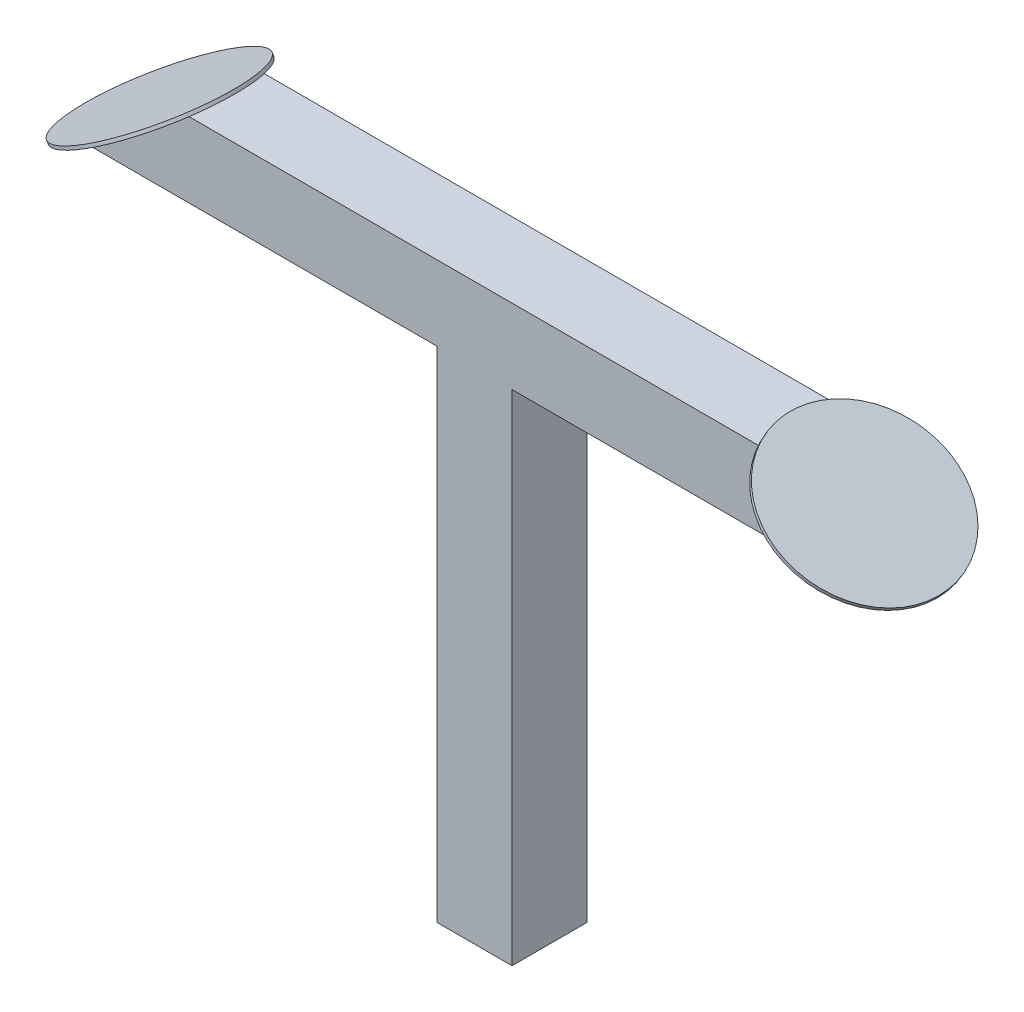
SolidWorks part; units mm, degrees
material "PVC Rigid"
ref_plane "Front Plane" through (0, 0, 0) normal (0, 0, 1) x (1, 0, 0)
ref_plane "Top Plane" through (0, 0, 0) normal (0, 1, 0) x (1, 0, 0)
ref_plane "Right Plane" through (0, 0, 0) normal (1, 0, 0) x (0, 0, -1)
sketch "Sketch1" plane through (0, 0, 0) normal (0, 1, 0) x (1, 0, 0)
  line L1 (-22.5, -22.5) -> (22.5, -22.5)
  line L2 (-22.5, -22.5) -> (-22.5, 22.5)
  line L3 (-22.5, 22.5) -> (22.5, 22.5)
  line L4 (22.5, -22.5) -> (22.5, 22.5)
  line L5 (-22.5, -22.5) -> (22.5, 22.5) construction
  line L6 (-22.5, 22.5) -> (22.5, -22.5) construction
  point P0 (0, 0)
  dimension "D1" = 45
  dimension "D2" = 45
extrude "Boss-Extrude1" add sketch "Sketch1" along normal blind 300
sketch "Sketch2" plane through (0, 300, 0) normal (0, 1, 0) x (1, 0, 0)
  line L1 (-250, -22.5) -> (250, -22.5)
  line L2 (-250, -22.5) -> (-250, 22.5)
  line L3 (-250, 22.5) -> (250, 22.5)
  line L4 (250, -22.5) -> (250, 22.5)
  line L5 (-250, -22.5) -> (250, 22.5) construction
  line L6 (-250, 22.5) -> (250, -22.5) construction
  point P0 (0, 0)
  dimension "D1" = 45
  dimension "D2" = 500
extrude "Boss-Extrude2" add sketch "Sketch2" along normal blind 45
shell "Shell2" thickness 5
sketch "Sketch4" plane through (0, 0, 22.5) normal (0, 0, 1) x (1, 0, 0)
  line L0 (-250, 300) -> (-172.0577, 345)
  line L1 (-250, 345) -> (250, 345) construction
  line L2 (-172.0577, 345) -> (-187.2638, 591.8178)
  line L3 (-187.2638, 591.8178) -> (-292.4022, 585.3404)
  line L4 (-292.4022, 585.3404) -> (-265.5442, 495.3628)
  line L5 (-265.5442, 495.3628) -> (-250, 300)
  line L6 (-250, 300) -> (-22.5, 300) construction
  dimension "D1" = 30
extrude "Cut-Extrude1" cut sketch "Sketch4" against normal blind 45
sketch "Sketch5" plane through (-192.4038, 333.2532, 0) normal (-0.5, 0.866, 0) x (0.866, 0.5, 0)
  line L0 (23.4936, 22.5) -> (-66.5064, -22.5) construction
  circle A0 centre (-21.5064, 0) radius 51.5
  dimension "D1" = 103
extrude "Boss-Extrude3" add sketch "Sketch5" along normal blind 2
mirror "Mirror1" about plane through (0, 0, 0) normal (1, 0, 0) of "Boss-Extrude3", "Cut-Extrude1"
